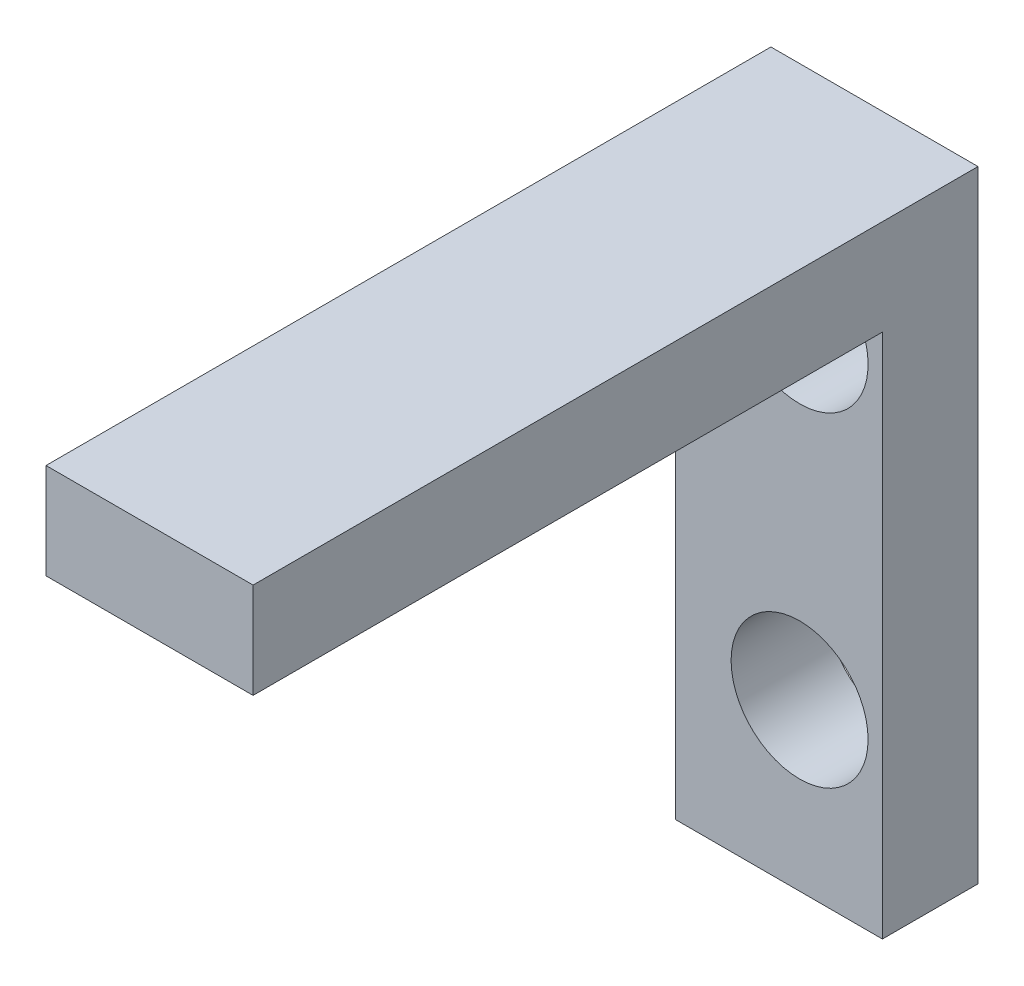
SolidWorks part; units mm, degrees
ref_plane "Front Plane" through (0, 0, 0) normal (0, 0, 1) x (1, 0, 0)
ref_plane "Top Plane" through (0, 0, 0) normal (0, 1, 0) x (1, 0, 0)
ref_plane "Right Plane" through (0, 0, 0) normal (1, 0, 0) x (0, 0, -1)
sketch "Sketch1" plane through (0, 0, 0) normal (0, 0, 1) x (1, 0, 0)
  line L0 (-27.5826, -109.1424) -> (-27.5826, 25.3696) construction
  line L1 (-34.0826, -6.4214) -> (-27.5826, -6.4214)
  line L2 (-34.0826, -6.4214) -> (-34.0826, -25.9214)
  line L3 (-34.0826, -25.9214) -> (-27.5826, -25.9214)
  line L4 (-27.5826, -6.4214) -> (-27.5826, -25.9214)
  line L5 (-34.0826, -10.6714) -> (-34.0826, -22.1714) construction
  line L6 (-34.7598, -25.9214) -> (-29.3942, -25.9214) construction
  line L7 (-27.5826, -6.4214) -> (-97.5826, -6.4214) construction
extrude "Boss-Extrude1" add sketch "Sketch1" along normal blind 3
sketch "Sketch6" plane through (0, -6.4214, 0) normal (0, 1, 0) x (1, 0, 0)
  line L0 (-27.5826, -3) -> (-27.5826, -22.7547)
  line L1 (-27.5826, -22.7547) -> (-34.0826, -22.7547)
  line L2 (-34.0826, -22.7547) -> (-34.0826, -3)
  line L3 (-27.5826, -3) -> (-34.0826, -3) construction
  line L4 (-27.5826, -3) -> (-34.0826, -3)
  dimension "D1" = 6.5
extrude "Boss-Extrude2" add sketch "Sketch6" against normal blind 3
sketch "Sketch7" plane through (0, 0, 0) normal (0, 0, -1) x (-1, 0, 0)
  line L0 (34.0826, -6.4214) -> (34.0826, -25.9214) construction
  line L1 (27.5826, -6.4214) -> (34.0826, -6.4214) construction
  line L2 (34.0826, -25.9214) -> (27.5826, -25.9214) construction
  circle A0 centre (30.1826, -10.5211) radius 2.15
  circle A1 centre (30.1826, -20.7211) radius 2.15
  dimension "D1" = 3.9
  dimension "D5" = 4.3
  dimension "D6" = 4.3
  dimension "D2" = 4.0997
  dimension "D3" = 3.9
  dimension "D4" = 5.2003
extrude "Cut-Extrude1" cut sketch "Sketch7" against normal blind 11
